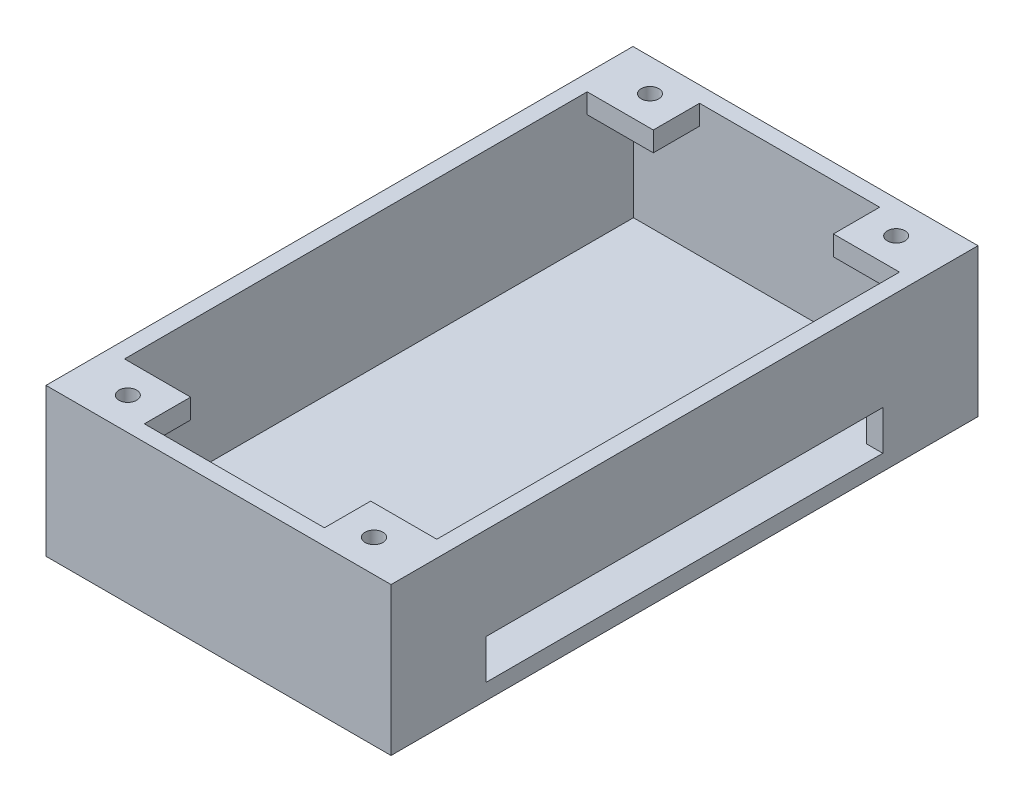
SolidWorks part; units mm, degrees
material "ABS"
ref_plane "Front Plane" through (0, 0, 0) normal (0, 0, 1) x (1, 0, 0)
ref_plane "Top Plane" through (0, 0, 0) normal (0, 1, 0) x (1, 0, 0)
ref_plane "Right Plane" through (0, 0, 0) normal (1, 0, 0) x (0, 0, -1)
sketch "Sketch1" plane through (0, 0, 0) normal (0, 1, 0) x (1, 0, 0)
  line L0 (-33.147, 56.388) -> (33.147, 56.388)
  line L1 (-30.099, 53.34) -> (30.099, 53.34)
  line L2 (-30.099, 53.34) -> (-30.099, -53.34)
  line L3 (-30.099, -53.34) -> (30.099, -53.34)
  line L4 (30.099, 53.34) -> (30.099, -53.34)
  line L5 (-30.099, 53.34) -> (30.099, -53.34) construction
  line L6 (-30.099, -53.34) -> (30.099, 53.34) construction
  line L7 (33.147, 56.388) -> (33.147, -56.388)
  line L8 (-33.147, -56.388) -> (33.147, -56.388)
  line L9 (-33.147, 56.388) -> (-33.147, -56.388)
  point P0 (0, 0)
  dimension "D1" = 60.198
  dimension "D2" = 106.68
  dimension "D3" = 3.048
extrude "Boss-Extrude1" add sketch "Sketch1" along normal blind 3.048 contours L9 L8 L7 L0
sketch "Sketch2" plane through (0, 3.048, 0) normal (0, 1, 0) x (1, 0, 0)
  line L1 (-33.147, 56.388) -> (33.147, 56.388)
  line L2 (-33.147, 56.388) -> (-33.147, -56.388)
  line L3 (-33.147, -56.388) -> (33.147, -56.388)
  line L4 (33.147, 56.388) -> (33.147, -56.388)
  line L5 (-33.147, 56.388) -> (33.147, -56.388) construction
  line L6 (-33.147, -56.388) -> (33.147, 56.388) construction
  line L7 (-30, 53.34) -> (30, 53.34)
  line L8 (-30, 53.34) -> (-30, -53.34)
  line L9 (-30, -53.34) -> (30, -53.34)
  line L10 (30, 53.34) -> (30, -53.34)
  line L11 (-30, 53.34) -> (30, -53.34) construction
  line L12 (-30, -53.34) -> (30, 53.34) construction
  point P0 (0, 0)
  point P7 (0, 0)
  dimension "D1" = 106.68
  dimension "D2" = 60
extrude "Boss-Extrude2" add sketch "Sketch2" along normal blind 25.4
sketch "Sketch3" plane through (0, 28.448, 0) normal (0, 1, 0) x (1, 0, 0)
  line L1 (-30, 53.34) -> (-17.3, 53.34)
  line L2 (-30, 53.34) -> (-30, 44.45)
  line L3 (-30, 44.45) -> (-17.3, 44.45)
  line L4 (-17.3, 53.34) -> (-17.3, 44.45)
  line L5 (-30, -53.34) -> (-17.3, -53.34)
  line L6 (-30, -53.34) -> (-30, -44.45)
  line L7 (-30, -44.45) -> (-17.3, -44.45)
  line L8 (-17.3, -53.34) -> (-17.3, -44.45)
  line L9 (30, 53.34) -> (17.3, 53.34)
  line L10 (30, 53.34) -> (30, 44.45)
  line L11 (30, 44.45) -> (17.3, 44.45)
  line L12 (17.3, 53.34) -> (17.3, 44.45)
  line L13 (30, -53.34) -> (17.3, -53.34)
  line L14 (30, -53.34) -> (30, -44.45)
  line L15 (30, -44.45) -> (17.3, -44.45)
  line L16 (17.3, -53.34) -> (17.3, -44.45)
  point P20 (-23.65, 47.625)
  point P21 (-23.65, -50.165)
  point P22 (23.65, -50.165)
  point P23 (23.65, 50.165)
  dimension "D1" = 12.7
  dimension "D2" = 8.89
  dimension "D3" = 8.89
  dimension "D4" = 12.7
  dimension "D5" = 12.7
  dimension "D6" = 8.89
  dimension "D7" = 8.89
  dimension "D8" = 12.7
  dimension "D9" = 6.35
  dimension "D10" = 3.175
  dimension "D11" = 6.35
  dimension "D12" = 3.175
  dimension "D13" = 6.35
  dimension "D14" = 3.175
  dimension "D15" = 6.35
  dimension "D16" = 3.175
extrude "Boss-Extrude3" add sketch "Sketch3" against normal blind 3.81
sketch "Sketch4" plane through (0, 28.448, 0) normal (0, 1, 0) x (1, 0, 0)
  line L0 (-17.3, 44.45) -> (-17.3, 53.34) construction
  line L3 (-17.3, -53.34) -> (-17.3, -44.45) construction
  line L4 (17.3, -44.45) -> (17.3, -53.34) construction
  line L7 (17.3, 53.34) -> (17.3, 44.45) construction
  line L9 (17.3, 53.34) -> (-17.3, 53.34) construction
  line L10 (-30, -53.34) -> (30, -53.34) construction
  line L11 (30, 53.34) -> (-30, 53.34) construction
  line L12 (-17.3, -53.34) -> (17.3, -53.34) construction
  circle A0 centre (-23.65, 50.165) radius 1.7
  circle A1 centre (23.65, 50.165) radius 1.7
  circle A2 centre (23.65, -50.165) radius 1.72
  circle A3 centre (-23.65, -50.165) radius 1.7
  point P0 (-23.65, 50.165)
  point P1 (-23.65, -50.165)
  point P2 (23.65, -50.165)
  point P3 (23.65, 50.165)
  dimension "D9" = 3.4
  dimension "D10" = 3.4
  dimension "D11" = 3.4
  dimension "D12" = 3.44
  dimension "D1" = 6.35
  dimension "D2" = 3.175
  dimension "D3" = 3.175
  dimension "D4" = 6.35
  dimension "D5" = 6.35
  dimension "D6" = 3.175
  dimension "D7" = 3.175
  dimension "D8" = 6.35
sketch "Sketch6" plane through (33.147, 0, 0) normal (1, 0, 0) x (0, 0, -1)
  line L1 (-38.1, 3.048) -> (38.1, 3.048)
  line L2 (-38.1, 3.048) -> (-38.1, 10.668)
  line L3 (-38.1, 10.668) -> (38.1, 10.668)
  line L4 (38.1, 3.048) -> (38.1, 10.668)
  line L6 (56.388, 0) -> (-56.388, 0) construction
  point P6 (0, 3.048)
  dimension "D1" = 7.62
  dimension "D2" = 3.048
  dimension "D3" = 76.2
extrude "Cut-Extrude1" cut sketch "Sketch6" against normal up to next
sketch "Sketch7" plane through (0, 0, 0) normal (0, -1, 0) x (1, 0, 0)
  line L1 (-25.4, 21.35) -> (25.4, 21.35)
  line L2 (-25.4, 21.35) -> (-25.4, -21.35)
  line L3 (-25.4, -21.35) -> (25.4, -21.35)
  line L4 (25.4, 21.35) -> (25.4, -21.35)
  line L5 (-25.4, 21.35) -> (25.4, -21.35) construction
  line L6 (-25.4, -21.35) -> (25.4, 21.35) construction
  point P0 (0, 0)
  dimension "D1" = 42.7
  dimension "D2" = 50.8
extrude "Boss-Extrude4" add sketch "Sketch7" along normal blind 6.35
sketch "Sketch8" plane through (0, 0, 21.35) normal (0, 0, 1) x (1, 0, 0)
  line L0 (-3.81, 0) -> (-3.81, -3.175)
  line L3 (25.4, 0) -> (-25.4, 0) construction
  line L4 (-3.81, -3.175) -> (-11.43, -3.175)
  line L5 (-11.43, -3.175) -> (-11.43, -6.35)
  line L6 (25.4, -6.35) -> (-25.4, -6.35) construction
  line L7 (-11.43, -6.35) -> (11.43, -6.35)
  line L8 (11.43, -6.35) -> (11.43, -3.175)
  line L9 (11.43, -3.175) -> (3.81, -3.175)
  line L10 (3.81, -3.175) -> (3.81, 0)
  line M5 (25.4, 0) -> (-25.4, 0)
  line M6 (-25.4, 0) -> (-25.4, -6.35)
  line M7 (-25.4, -6.35) -> (25.4, -6.35)
  line M8 (25.4, -6.35) -> (25.4, 0)
  dimension "D1" = 3.81
  dimension "D2" = 3.81
  dimension "D3" = 7.62
  dimension "D4" = 7.62
  dimension "D5" = 3.175
  dimension "D6" = 3.175
extrude "Cut-Extrude2" cut sketch "Sketch8" against normal through all and the other way through all contours L5 L4 L0 M5 M6 M7 | L10 L9 L8 M7 M8 M5
sketch "Sketch9" plane through (0, -6.35, 0) normal (0, -1, 0) x (1, 0, 0)
  line L0 (-11.43, 21.35) -> (-11.43, -21.35) construction
  line L1 (-11.43, 11.65) -> (11.43, 11.65)
  line L2 (-11.43, 11.65) -> (-11.43, 21.35)
  line L3 (-11.43, 21.35) -> (11.43, 21.35)
  line L4 (11.43, 11.65) -> (11.43, 21.35)
  dimension "D1" = 9.7
extrude "Cut-Extrude3" cut sketch "Sketch9" against normal up to surface (6.35 mm away)
extrude "Cut-Extrude4" cut sketch "Sketch4" against normal up to next contours A1 | A2 | A3 | A0
